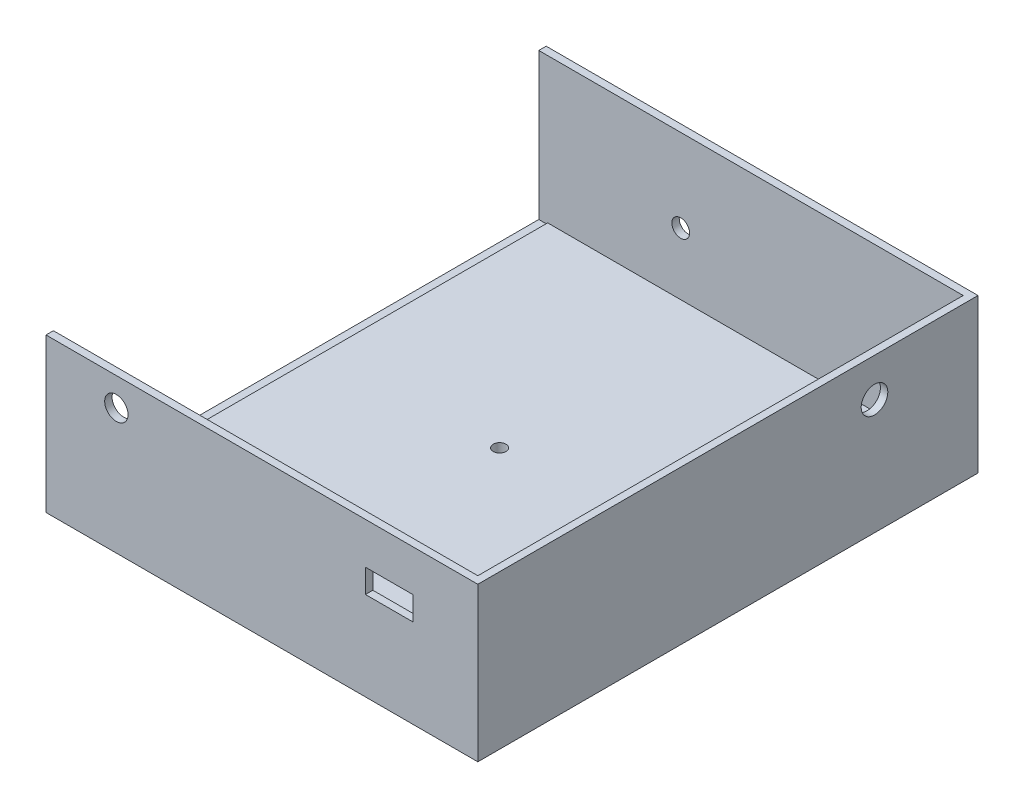
SolidWorks part; units mm, degrees
ref_plane "Front Plane" through (0, 0, 0) normal (0, 0, 1) x (1, 0, 0)
ref_plane "Top Plane" through (0, 0, 0) normal (0, 1, 0) x (1, 0, 0)
ref_plane "Right Plane" through (0, 0, 0) normal (1, 0, 0) x (0, 0, -1)
sketch "Sketch1" plane through (0, 0, 0) normal (0, 1, 0) x (1, 0, 0)
  line L1 (-90.1301, 96.0179) -> (55.8999, 96.0179)
  line L2 (-90.1301, 96.0179) -> (-90.1301, -73.1221)
  line L3 (-90.1301, -73.1221) -> (55.8999, -73.1221)
  line L4 (55.8999, 96.0179) -> (55.8999, -73.1221)
  dimension "D1" = 169.14
  dimension "D2" = 146.03
extrude "Boss-Extrude2" add sketch "Sketch1" along normal blind 52 contours L2 L3 L4 L1
sketch "Sketch6" plane through (0, 52, 0) normal (0, 1, 0) x (1, 0, 0)
  line L0 (-90.1301, 96.0179) -> (-90.1301, -73.1221) construction
  line L1 (-87.6301, 93.5179) -> (53.3999, 93.5179)
  line L2 (-87.6301, 93.5179) -> (-87.6301, -70.6221)
  line L3 (-87.6301, -70.6221) -> (53.3999, -70.6221)
  line L4 (53.3999, 93.5179) -> (53.3999, -70.6221)
  line L5 (-90.1301, 96.0179) -> (55.8999, 96.0179) construction
  dimension "D1" = 2.5
  dimension "D2" = 2.5
  dimension "D3" = 164.14
  dimension "D4" = 141.03
extrude "Cut-Extrude3" cut sketch "Sketch6" against normal blind 49 contours L2 L3 L4 L1
sketch "Sketch7" plane through (0, 3, 0) normal (0, 1, 0) x (1, 0, 0)
  line L0 (53.3999, 93.5179) -> (53.3999, -70.6221) construction
  line L1 (-87.6301, 93.5179) -> (53.3999, 93.5179) construction
  line L2 (53.3999, 93.5179) -> (53.3999, -70.6221) construction
  line L3 (-87.6301, -70.6221) -> (53.3999, -70.6221) construction
  line L4 (-87.6301, 93.5179) -> (-87.6301, -70.6221) construction
  line L5 (-87.6301, 93.5179) -> (53.3999, 93.5179) construction
  circle A0 centre (39.2399, -56.4621) radius 2.16
  circle A1 centre (39.2399, 79.3579) radius 2.16
  circle A2 centre (-29.3701, 19.5179) radius 2.16
  dimension "D1" = 14.16
  dimension "D2" = 14.16
  dimension "D3" = 14.16
  dimension "D4" = 14.16
  dimension "D5" = 58.26
  dimension "D6" = 74
extrude "Cut-Extrude4" cut sketch "Sketch7" against normal blind 50
sketch "Sketch8" plane through (55.8999, 0, 0) normal (1, 0, 0) x (0, 0, -1)
  line L0 (96.0179, 0) -> (-73.1221, 0) construction
  line L1 (96.0179, 52) -> (96.0179, 0) construction
  circle A0 centre (61.0179, 39) radius 4.5
  dimension "D1" = 39
  dimension "D2" = 35
extrude "Cut-Extrude5" cut sketch "Sketch8" against normal blind 2.5 contours A0
sketch "Sketch9" plane through (0, 0, 73.1221) normal (0, 0, 1) x (1, 0, 0)
  line L0 (-90.1301, 0) -> (55.8999, 0) construction
  line L1 (17.8999, 38) -> (33.8999, 38)
  line L2 (17.8999, 38) -> (17.8999, 30)
  line L3 (17.8999, 30) -> (33.8999, 30)
  line L4 (33.8999, 38) -> (33.8999, 30)
  line L5 (55.8999, 52) -> (55.8999, 0) construction
  dimension "D1" = 30
  dimension "D2" = 8
  dimension "D3" = 16
  dimension "D4" = 22
extrude "Cut-Extrude6" cut sketch "Sketch9" against normal blind 3 contours L2 L1 L4 L3
sketch "Sketch11" plane through (0, 0, -96.0179) normal (0, 0, -1) x (-1, 0, 0)
  line L0 (-55.8999, 52) -> (-55.8999, 0) construction
  line L1 (-53.3999, 52) -> (87.6301, 52)
  line L2 (-53.3999, 52) -> (-53.3999, 2.5)
  line L3 (-53.3999, 2.5) -> (87.6301, 2.5)
  line L4 (87.6301, 52) -> (87.6301, 2.5)
  line L5 (90.1301, 0) -> (-55.8999, 0) construction
  line L6 (90.1301, 52) -> (90.1301, 0) construction
  line L8 (90.1301, 52) -> (-55.8999, 52) construction
  dimension "D1" = 2.5
  dimension "D2" = 2.5
  dimension "D3" = 2.5
sketch "Sketch12" plane through (-90.1301, 0, 0) normal (-1, 0, 0) x (0, 0, 1)
  line L0 (-96.0179, 52) -> (-96.0179, 2.5) construction
  line L1 (-93.5179, 52) -> (70.6221, 52)
  line L2 (-93.5179, 52) -> (-93.5179, 2.5)
  line L3 (-93.5179, 2.5) -> (70.6221, 2.5)
  line L4 (70.6221, 52) -> (70.6221, 2.5)
  line L5 (-96.0179, 0) -> (73.1221, 0) construction
  line L6 (73.1221, 52) -> (73.1221, 0) construction
  line L7 (-96.0179, 52) -> (73.1221, 52) construction
  dimension "D1" = 2.5
  dimension "D2" = 2.5
  dimension "D3" = 2.5
extrude "Cut-Extrude9" cut sketch "Sketch12" against normal blind 3
sketch "Sketch13" plane through (0, 0, 73.1221) normal (0, 0, 1) x (1, 0, 0)
  line L0 (53.3999, 2.5) -> (-87.6301, 2.5) construction
  circle A0 centre (-66.3389, 42.5) radius 3.95
  dimension "D1" = 40
extrude "Cut-Extrude10" cut sketch "Sketch13" against normal blind 3
sketch "Sketch14" plane through (0, 0, -96.0179) normal (0, 0, -1) x (-1, 0, 0)
  line L0 (90.1301, 52) -> (90.1301, 0) construction
  line L1 (90.1301, 0) -> (-55.8999, 0) construction
  circle A0 centre (42.1301, 24) radius 3
  dimension "D1" = 48
  dimension "D2" = 24
extrude "Cut-Extrude11" cut sketch "Sketch14" against normal blind 3 contours A0
